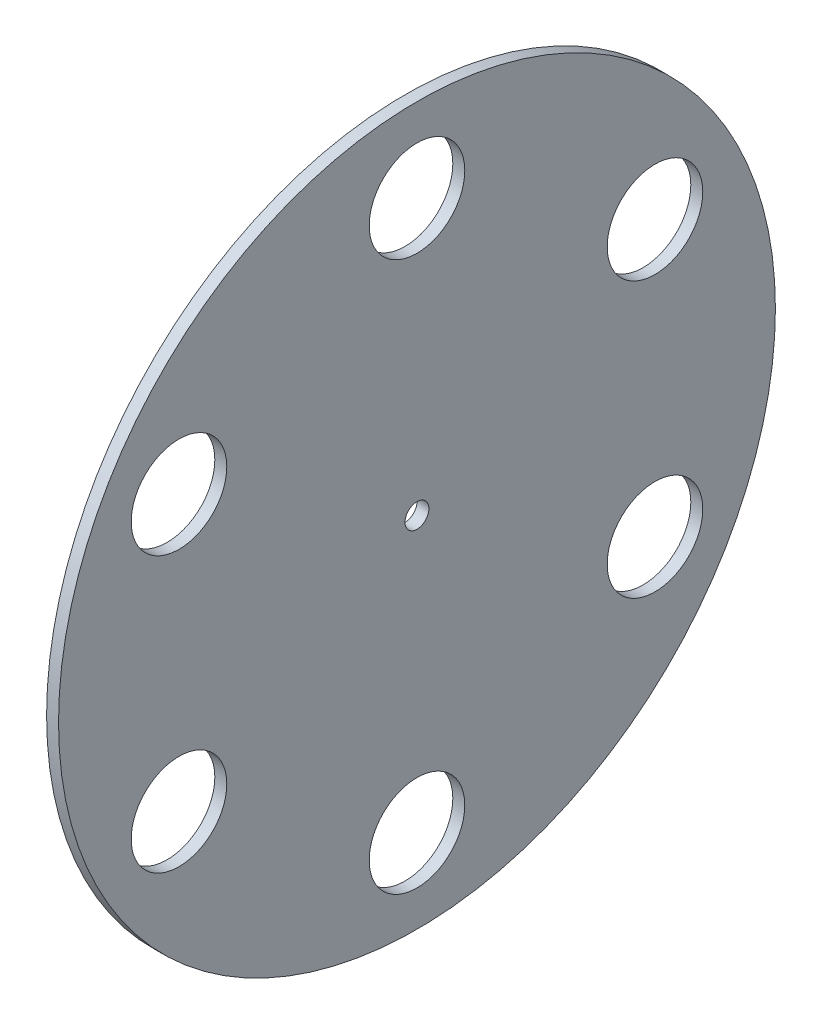
SolidWorks part; units mm, degrees
ref_plane "Front Plane" through (0, 0, 0) normal (0, 0, 1) x (1, 0, 0)
ref_plane "Top Plane" through (0, 0, 0) normal (0, 1, 0) x (1, 0, 0)
ref_plane "Right Plane" through (0, 0, 0) normal (1, 0, 0) x (0, 0, -1)
sketch "Sketch1" plane through (0, 0, 0) normal (1, 0, 0) x (0, 0, -1)
  line L0 (0, 0) -> (0, 300) construction
  line L1 (0, 0) -> (259.8076, 150) construction
  line L2 (0, 0) -> (259.8076, -150) construction
  line L3 (0, 0) -> (0, -300) construction
  line L4 (0, 0) -> (-259.8076, -150) construction
  line L5 (0, 0) -> (-259.8076, 150) construction
  circle A0 centre (0, 0) radius 300
  circle A1 centre (0, 0) radius 10
  circle A2 centre (0, 230) radius 40
  circle A3 centre (199.1858, 115) radius 40
  circle A4 centre (199.1858, -115) radius 40
  circle A5 centre (0, -230) radius 40
  circle A6 centre (-199.1858, -115) radius 40
  circle A7 centre (-199.1858, 115) radius 40
  point P13 (0, 0)
  point P26 (0, 0)
  dimension "D1" = 600
  dimension "D2" = 20
  dimension "D4" = 80
  dimension "D5" = 230
  dimension "D3" = 6
  dimension "D6" = 6
extrude "Boss-Extrude1" add sketch "Sketch1" along normal blind 10
ref_plane "Plane1" through (10, 0, 0) normal (-1, 0, 0) x (0, 0, 1)
